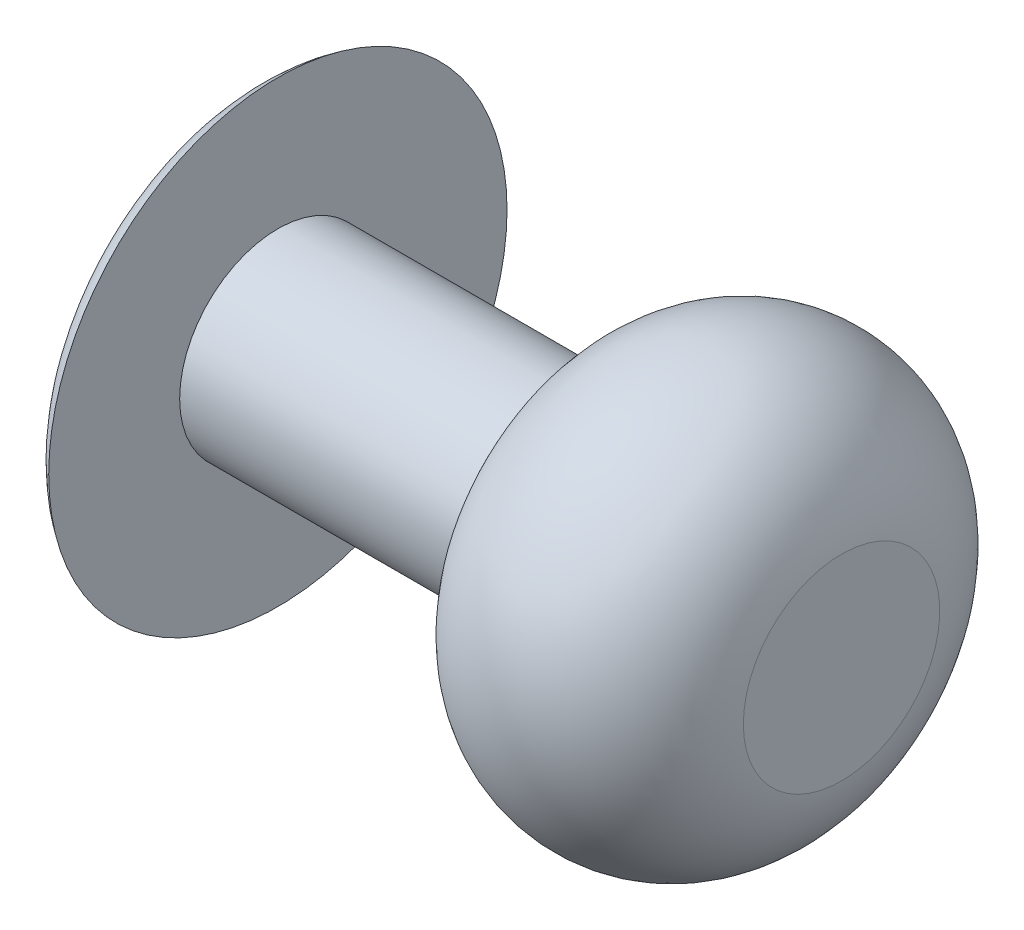
SolidWorks part; units mm, degrees
ref_plane "Plan de face" through (0, 0, 0) normal (0, 0, 1) x (1, 0, 0)
ref_plane "Plan de dessus" through (0, 0, 0) normal (0, 1, 0) x (1, 0, 0)
ref_plane "Plan de droite" through (0, 0, 0) normal (1, 0, 0) x (0, 0, -1)
sketch "Esquisse1" plane through (0, 0, 0) normal (0, 0, 1) x (1, 0, 0)
  line L0 (-91.1066, 0) -> (94.9883, 0) construction
  line L1 (-13.4906, 0) -> (-13.4906, 2.5)
  line L2 (-12.9389, 1.5) -> (-12.9389, 3.5)
  line L3 (-12.9389, 1.5) -> (-8.4389, 1.5)
  line L4 (-4.3301, 1.5) -> (-4.3301, 0)
  line L5 (-4.3301, 0) -> (-13.4906, 0)
  arc A0 (-12.9389, 3.5) -> (-13.4906, 2.5) centre (-12.3085, 2.5) ccw
  arc A1 (-4.3301, 1.5) -> (-8.4389, 1.5) centre (-6.3845, 1.205) ccw
  dimension "D1" = 2.5
  dimension "D2" = 1
  dimension "D3" = 4.5
  dimension "D4" = 1.5
  dimension "D5" = 1.5
revolve "Révolution1" add sketch "Esquisse1" angle 360 about L0
sketch "Esquisse2" plane through (-13.4906, 0, 0) normal (-1, 0, 0) x (0, 0, 1)
  circle A0 centre (0, 0) radius 1
  dimension "D1" = 2
extrude "Extrusion1" cut sketch "Esquisse2" against normal blind 4
